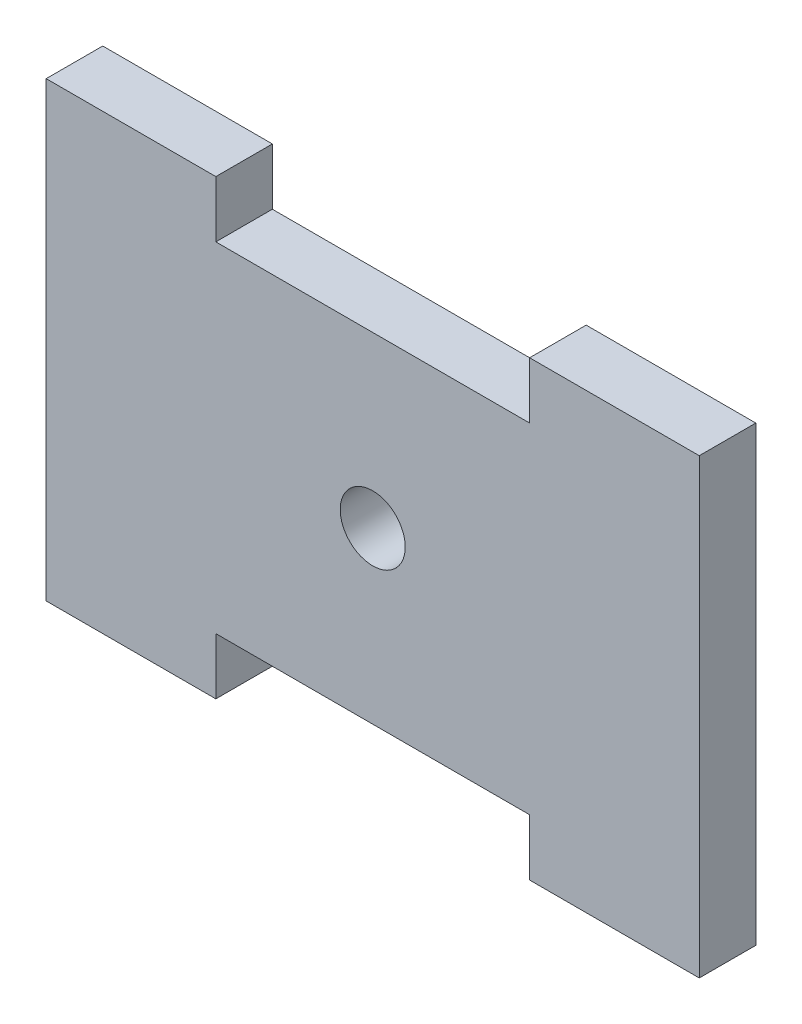
SolidWorks part; units mm, degrees
ref_plane "前视基准面" through (0, 0, 0) normal (0, 0, 1) x (1, 0, 0)
ref_plane "上视基准面" through (0, 0, 0) normal (0, 1, 0) x (1, 0, 0)
ref_plane "右视基准面" through (0, 0, 0) normal (1, 0, 0) x (0, 0, -1)
sketch "草图1" plane through (0, 0, 0) normal (0, 0, 1) x (1, 0, 0)
  line L0 (0, 0) -> (17.1, 0) construction
  line L1 (8.55, 0) -> (8.55, 1.7609) construction
  line L2 (-3, 1) -> (3, 1)
  line L3 (-3, 1) -> (-3, -1)
  line L4 (-3, -1) -> (3, -1) construction
  line L5 (3, 1) -> (3, -1)
  line L6 (-3, 1) -> (3, -1) construction
  line L7 (-3, -1) -> (3, 1) construction
  line L8 (14.1, 1) -> (14.1, -1)
  line L9 (20.1, 1) -> (20.1, -1)
  line L10 (20.1, 1) -> (14.1, 1)
  line L12 (-4.7034, -7) -> (23.2867, -7) construction
  line L13 (-3, -13) -> (3, -15) construction
  line L14 (-3, -15) -> (3, -13) construction
  line L15 (-3, -13) -> (3, -13) construction
  line L16 (8.55, -14) -> (8.55, -15.7609) construction
  line L17 (0, -14) -> (17.1, -14) construction
  line L19 (20.1, -15) -> (14.1, -15)
  line L20 (20.1, -15) -> (20.1, -13)
  line L21 (14.1, -15) -> (14.1, -13)
  line L22 (3, -15) -> (3, -13)
  line L23 (-3, -15) -> (-3, -13)
  line L24 (-3, -15) -> (3, -15)
  line L25 (-3, -13) -> (-3, -1)
  line L26 (20.1, -1) -> (20.1, -13)
  line L27 (8.55, 5.1) -> (8.55, -19.1) construction
  line L28 (6.45, -1) -> (6.45, -4.2) construction
  line L29 (6.45, -4.2) -> (5.05, -4.2) construction
  line L30 (5.05, -4.2) -> (5.05, -7.4) construction
  line L31 (5.05, -7.4) -> (12.05, -7.4) construction
  line L32 (3, -1) -> (6.45, -1) construction
  line L33 (14.1, -1) -> (10.65, -1) construction
  line L34 (10.65, -4.2) -> (12.05, -4.2) construction
  line L35 (12.05, -4.2) -> (12.05, -7.4) construction
  line L36 (10.65, -1) -> (10.65, -4.2) construction
  line L37 (3, -13) -> (6.45, -13) construction
  line L38 (14.1, -13) -> (10.65, -13) construction
  line L39 (10.65, -13) -> (10.65, -9.8) construction
  line L40 (6.45, -13) -> (6.45, -9.8) construction
  line L41 (6.45, -9.8) -> (5.05, -9.8) construction
  line L42 (10.65, -9.8) -> (12.05, -9.8)
  line L43 (12.05, -9.8) -> (12.05, -6.6) construction
  line L44 (5.05, -9.8) -> (5.05, -6.6) construction
  line L45 (5.05, -6.6) -> (12.05, -6.6) construction
  line L46 (3, -1) -> (14.1, -1)
  line L47 (3, -13) -> (14.1, -13)
  circle A0 centre (8.55, -7) radius 1.15
  point P40 (8.55, -7.4)
  point P48 (0, 0)
  point P49 (8.55, -7)
  dimension "D5" = 3.5
  dimension "D1" = 17.1
  dimension "D2" = 2
  dimension "D3" = 6
  dimension "D4" = 3.2
  dimension "D6" = 2.1
  dimension "D7" = 12
extrude "凸台-拉伸1" add sketch "草图1" along normal blind 2
